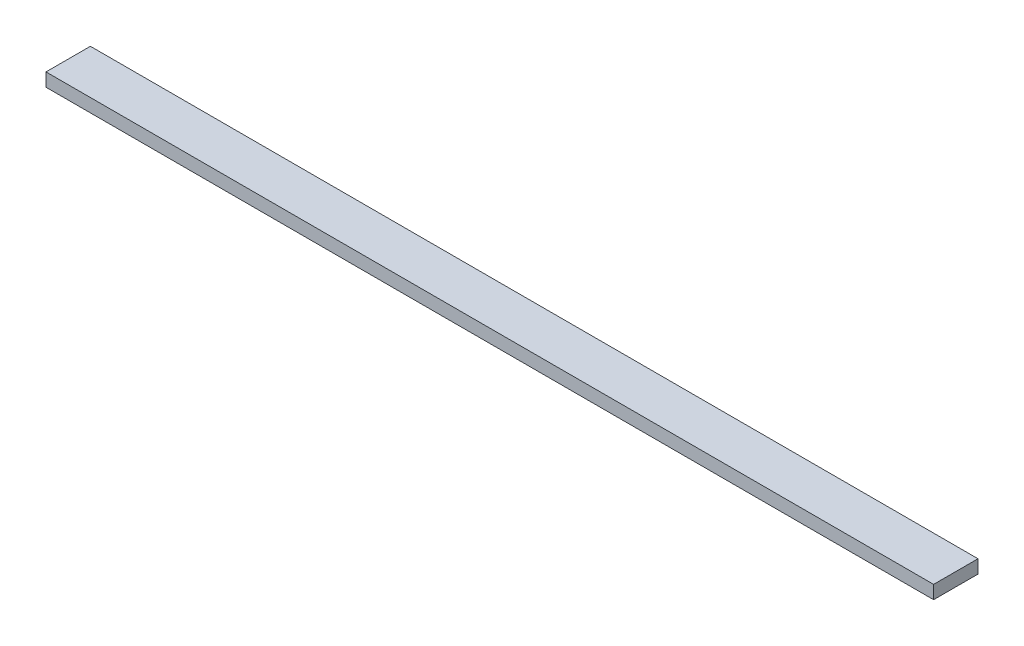
SolidWorks part; units mm, degrees
ref_plane "Front Plane" through (0, 0, 0) normal (0, 0, 1) x (1, 0, 0)
ref_plane "Top Plane" through (0, 0, 0) normal (0, 1, 0) x (1, 0, 0)
ref_plane "Right Plane" through (0, 0, 0) normal (1, 0, 0) x (0, 0, -1)
sketch "Sketch1" plane through (0, 0, 0) normal (0, 1, 0) x (1, 0, 0)
  line L1 (-100, -5) -> (100, -5)
  line L2 (-100, -5) -> (-100, 5)
  line L3 (-100, 5) -> (100, 5)
  line L4 (100, -5) -> (100, 5)
  line L5 (-100, -5) -> (100, 5) construction
  line L6 (-100, 5) -> (100, -5) construction
  point P0 (0, 0)
  dimension "D1" = 10
  dimension "D2" = 200
extrude "Boss-Extrude1" add sketch "Sketch1" along normal mid plane 3
